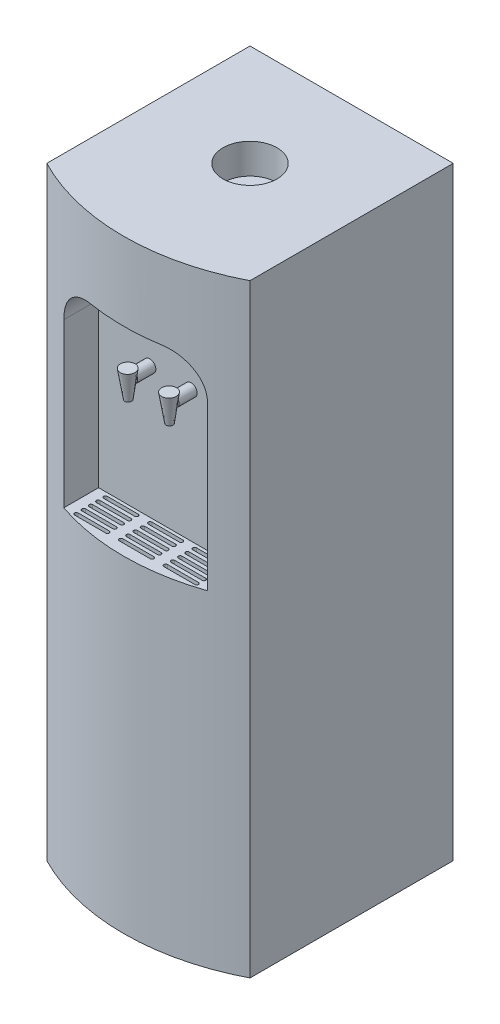
SolidWorks part; units mm, degrees
ref_plane "Front Plane" through (0, 0, 0) normal (0, 0, 1) x (1, 0, 0)
ref_plane "Top Plane" through (0, 0, 0) normal (0, 1, 0) x (1, 0, 0)
ref_plane "Right Plane" through (0, 0, 0) normal (1, 0, 0) x (0, 0, -1)
sketch "Sketch1" plane through (0, 0, 0) normal (0, 1, 0) x (1, 0, 0)
  line L1 (0, 0) -> (42.7396, 0)
  line L2 (0, 0) -> (0, -42.7396)
  line L4 (42.7396, 0) -> (42.7396, -42.7396)
  arc A0 (0, -42.7396) -> (42.7396, -42.7396) centre (21.3698, -1.442) ccw
extrude "Boss-Extrude1" add sketch "Sketch1" along normal blind 127
ref_plane "Plane1" through (0, 0, 127) normal (0, 0, 1) x (1, 0, 0)
sketch "Sketch2" plane through (0, 0, 127) normal (0, 0, 1) x (1, 0, 0)
  line L0 (6.2617, 110.6088) -> (0, 110.6088) construction
  line L1 (13.8817, 110.6088) -> (28.8579, 110.6088)
  line L2 (6.2617, 102.9888) -> (6.2617, 68.7343)
  line L3 (6.2617, 68.7343) -> (36.4779, 68.7343)
  line L4 (36.4779, 102.9888) -> (36.4779, 68.7343)
  line L5 (0, 127) -> (0, 0) construction
  line L6 (36.4779, 110.6088) -> (42.7396, 110.6088) construction
  line L7 (42.7396, 127) -> (42.7396, 0) construction
  arc A0 (28.8579, 110.6088) -> (36.4779, 102.9888) centre (28.8579, 102.9888) cw
  arc A1 (13.8817, 110.6088) -> (6.2617, 102.9888) centre (13.8817, 102.9888) ccw
  dimension "D1" = 7.62
extrude "Cut-Extrude1" cut sketch "Sketch2" against normal blind 88.9
sketch "Sketch4" plane through (0, 68.7343, 0) normal (0, 1, 0) x (1, 0, 0)
  line L0 (6.2617, -38.1) -> (36.4779, -38.1) construction
  line L1 (6.2617, -38.1) -> (36.4779, -38.1) construction
  line L2 (36.4779, -38.1) -> (36.4779, -45.4182) construction
  line L3 (6.2617, -38.1) -> (6.2617, -45.4182) construction
  line L4 (8.7222, -40.6541) -> (15.2596, -40.6541) construction
  line L5 (8.7222, -40.2731) -> (15.2596, -40.2731)
  line L6 (8.7222, -41.0351) -> (15.2596, -41.0351)
  line L7 (18.1011, -40.6541) -> (24.6385, -40.6541) construction
  line L8 (18.1011, -40.2731) -> (24.6385, -40.2731)
  line L9 (18.1011, -41.0351) -> (24.6385, -41.0351)
  line L10 (27.48, -40.6541) -> (34.0174, -40.6541) construction
  line L11 (27.48, -40.2731) -> (34.0174, -40.2731)
  line L12 (27.48, -41.0351) -> (34.0174, -41.0351)
  line L13 (8.3412, -40.6541) -> (6.2617, -40.6541) construction
  line L14 (34.3984, -40.6541) -> (36.4779, -40.6541) construction
  line L15 (15.6406, -40.6541) -> (17.7201, -40.6541) construction
  line L16 (25.0195, -40.6541) -> (27.099, -40.6541) construction
  line L17 (8.7222, -42.1781) -> (15.2596, -42.1781) construction
  line L18 (8.7222, -41.7971) -> (15.2596, -41.7971)
  line L19 (8.7222, -42.5591) -> (15.2596, -42.5591)
  line L20 (18.1011, -42.1781) -> (24.6385, -42.1781) construction
  line L21 (18.1011, -41.7971) -> (24.6385, -41.7971)
  line L22 (18.1011, -42.5591) -> (24.6385, -42.5591)
  line L23 (27.48, -42.1781) -> (34.0174, -42.1781) construction
  line L24 (27.48, -41.7971) -> (34.0174, -41.7971)
  line L25 (27.48, -42.5591) -> (34.0174, -42.5591)
  line L26 (8.7222, -43.7021) -> (15.2596, -43.7021) construction
  line L27 (8.7222, -43.3211) -> (15.2596, -43.3211)
  line L28 (8.7222, -44.0831) -> (15.2596, -44.0831)
  line L29 (18.1011, -43.7021) -> (24.6385, -43.7021) construction
  line L30 (18.1011, -43.3211) -> (24.6385, -43.3211)
  line L31 (18.1011, -44.0831) -> (24.6385, -44.0831)
  line L32 (27.48, -43.7021) -> (34.0174, -43.7021) construction
  line L33 (27.48, -43.3211) -> (34.0174, -43.3211)
  line L34 (27.48, -44.0831) -> (34.0174, -44.0831)
  line L35 (8.7222, -45.2261) -> (15.2596, -45.2261) construction
  line L36 (8.7222, -44.8451) -> (15.2596, -44.8451)
  line L37 (8.7222, -45.6071) -> (15.2596, -45.6071)
  line L38 (18.1011, -45.2261) -> (24.6385, -45.2261) construction
  line L39 (18.1011, -44.8451) -> (24.6385, -44.8451)
  line L40 (18.1011, -45.6071) -> (24.6385, -45.6071)
  line L41 (27.48, -45.2261) -> (34.0174, -45.2261) construction
  line L42 (27.48, -44.8451) -> (34.0174, -44.8451)
  line L43 (27.48, -45.6071) -> (34.0174, -45.6071)
  line L44 (8.7222, -40.6541) -> (15.2596, -40.6541) construction
  line L45 (8.7222, -40.2731) -> (15.2596, -40.2731)
  line L46 (8.7222, -41.0351) -> (15.2596, -41.0351)
  line L47 (18.1011, -40.6541) -> (24.6385, -40.6541) construction
  line L48 (18.1011, -40.2731) -> (24.6385, -40.2731)
  line L49 (18.1011, -41.0351) -> (24.6385, -41.0351)
  line L50 (27.48, -40.6541) -> (34.0174, -40.6541) construction
  line L51 (27.48, -40.2731) -> (34.0174, -40.2731)
  line L52 (27.48, -41.0351) -> (34.0174, -41.0351)
  line L53 (8.7222, -42.1781) -> (15.2596, -42.1781) construction
  line L54 (8.7222, -41.7971) -> (15.2596, -41.7971)
  line L55 (8.7222, -42.5591) -> (15.2596, -42.5591)
  line L56 (18.1011, -42.1781) -> (24.6385, -42.1781) construction
  line L57 (18.1011, -41.7971) -> (24.6385, -41.7971)
  line L58 (18.1011, -42.5591) -> (24.6385, -42.5591)
  line L59 (27.48, -42.1781) -> (34.0174, -42.1781) construction
  line L60 (27.48, -41.7971) -> (34.0174, -41.7971)
  line L61 (27.48, -42.5591) -> (34.0174, -42.5591)
  line L62 (8.7222, -43.7021) -> (15.2596, -43.7021) construction
  line L63 (8.7222, -43.3211) -> (15.2596, -43.3211)
  line L64 (8.7222, -44.0831) -> (15.2596, -44.0831)
  line L65 (18.1011, -43.7021) -> (24.6385, -43.7021) construction
  line L66 (18.1011, -43.3211) -> (24.6385, -43.3211)
  line L67 (18.1011, -44.0831) -> (24.6385, -44.0831)
  line L68 (27.48, -43.7021) -> (34.0174, -43.7021) construction
  line L69 (27.48, -43.3211) -> (34.0174, -43.3211)
  line L70 (27.48, -44.0831) -> (34.0174, -44.0831)
  line L71 (8.7222, -39.1301) -> (15.2596, -39.1301) construction
  line L72 (8.7222, -38.7491) -> (15.2596, -38.7491)
  line L73 (8.7222, -39.5111) -> (15.2596, -39.5111)
  line L74 (18.1011, -39.1301) -> (24.6385, -39.1301) construction
  line L75 (18.1011, -38.7491) -> (24.6385, -38.7491)
  line L76 (18.1011, -39.5111) -> (24.6385, -39.5111)
  line L77 (27.48, -39.1301) -> (34.0174, -39.1301) construction
  line L78 (27.48, -38.7491) -> (34.0174, -38.7491)
  line L79 (27.48, -39.5111) -> (34.0174, -39.5111)
  arc A0 (8.7222, -40.2731) -> (8.7222, -41.0351) centre (8.7222, -40.6541) ccw
  arc A1 (15.2596, -41.0351) -> (15.2596, -40.2731) centre (15.2596, -40.6541) ccw
  arc A2 (18.1011, -40.2731) -> (18.1011, -41.0351) centre (18.1011, -40.6541) ccw
  arc A3 (24.6385, -41.0351) -> (24.6385, -40.2731) centre (24.6385, -40.6541) ccw
  arc A4 (27.48, -40.2731) -> (27.48, -41.0351) centre (27.48, -40.6541) ccw
  arc A5 (34.0174, -41.0351) -> (34.0174, -40.2731) centre (34.0174, -40.6541) ccw
  arc A6 (8.7222, -41.7971) -> (8.7222, -42.5591) centre (8.7222, -42.1781) ccw
  arc A7 (15.2596, -42.5591) -> (15.2596, -41.7971) centre (15.2596, -42.1781) ccw
  arc A8 (18.1011, -41.7971) -> (18.1011, -42.5591) centre (18.1011, -42.1781) ccw
  arc A9 (24.6385, -42.5591) -> (24.6385, -41.7971) centre (24.6385, -42.1781) ccw
  arc A10 (27.48, -41.7971) -> (27.48, -42.5591) centre (27.48, -42.1781) ccw
  arc A11 (34.0174, -42.5591) -> (34.0174, -41.7971) centre (34.0174, -42.1781) ccw
  arc A12 (8.7222, -43.3211) -> (8.7222, -44.0831) centre (8.7222, -43.7021) ccw
  arc A13 (15.2596, -44.0831) -> (15.2596, -43.3211) centre (15.2596, -43.7021) ccw
  arc A14 (18.1011, -43.3211) -> (18.1011, -44.0831) centre (18.1011, -43.7021) ccw
  arc A15 (24.6385, -44.0831) -> (24.6385, -43.3211) centre (24.6385, -43.7021) ccw
  arc A16 (27.48, -43.3211) -> (27.48, -44.0831) centre (27.48, -43.7021) ccw
  arc A17 (34.0174, -44.0831) -> (34.0174, -43.3211) centre (34.0174, -43.7021) ccw
  arc A18 (8.7222, -44.8451) -> (8.7222, -45.6071) centre (8.7222, -45.2261) ccw
  arc A19 (15.2596, -45.6071) -> (15.2596, -44.8451) centre (15.2596, -45.2261) ccw
  arc A20 (18.1011, -44.8451) -> (18.1011, -45.6071) centre (18.1011, -45.2261) ccw
  arc A21 (24.6385, -45.6071) -> (24.6385, -44.8451) centre (24.6385, -45.2261) ccw
  arc A22 (27.48, -44.8451) -> (27.48, -45.6071) centre (27.48, -45.2261) ccw
  arc A23 (34.0174, -45.6071) -> (34.0174, -44.8451) centre (34.0174, -45.2261) ccw
  arc A24 (8.7222, -40.2731) -> (8.7222, -41.0351) centre (8.7222, -40.6541) ccw
  arc A25 (15.2596, -41.0351) -> (15.2596, -40.2731) centre (15.2596, -40.6541) ccw
  arc A26 (18.1011, -40.2731) -> (18.1011, -41.0351) centre (18.1011, -40.6541) ccw
  arc A27 (24.6385, -41.0351) -> (24.6385, -40.2731) centre (24.6385, -40.6541) ccw
  arc A28 (27.48, -40.2731) -> (27.48, -41.0351) centre (27.48, -40.6541) ccw
  arc A29 (34.0174, -41.0351) -> (34.0174, -40.2731) centre (34.0174, -40.6541) ccw
  arc A30 (8.7222, -41.7971) -> (8.7222, -42.5591) centre (8.7222, -42.1781) ccw
  arc A31 (15.2596, -42.5591) -> (15.2596, -41.7971) centre (15.2596, -42.1781) ccw
  arc A32 (18.1011, -41.7971) -> (18.1011, -42.5591) centre (18.1011, -42.1781) ccw
  arc A33 (24.6385, -42.5591) -> (24.6385, -41.7971) centre (24.6385, -42.1781) ccw
  arc A34 (27.48, -41.7971) -> (27.48, -42.5591) centre (27.48, -42.1781) ccw
  arc A35 (34.0174, -42.5591) -> (34.0174, -41.7971) centre (34.0174, -42.1781) ccw
  arc A36 (8.7222, -43.3211) -> (8.7222, -44.0831) centre (8.7222, -43.7021) ccw
  arc A37 (15.2596, -44.0831) -> (15.2596, -43.3211) centre (15.2596, -43.7021) ccw
  arc A38 (18.1011, -43.3211) -> (18.1011, -44.0831) centre (18.1011, -43.7021) ccw
  arc A39 (24.6385, -44.0831) -> (24.6385, -43.3211) centre (24.6385, -43.7021) ccw
  arc A40 (27.48, -43.3211) -> (27.48, -44.0831) centre (27.48, -43.7021) ccw
  arc A41 (34.0174, -44.0831) -> (34.0174, -43.3211) centre (34.0174, -43.7021) ccw
  arc A42 (8.7222, -38.7491) -> (8.7222, -39.5111) centre (8.7222, -39.1301) ccw
  arc A43 (15.2596, -39.5111) -> (15.2596, -38.7491) centre (15.2596, -39.1301) ccw
  arc A44 (18.1011, -38.7491) -> (18.1011, -39.5111) centre (18.1011, -39.1301) ccw
  arc A45 (24.6385, -39.5111) -> (24.6385, -38.7491) centre (24.6385, -39.1301) ccw
  arc A46 (27.48, -38.7491) -> (27.48, -39.5111) centre (27.48, -39.1301) ccw
  arc A47 (34.0174, -39.5111) -> (34.0174, -38.7491) centre (34.0174, -39.1301) ccw
  point P12 (11.9909, -40.6541)
  point P17 (21.3698, -40.6541)
  point P26 (30.7487, -40.6541)
  point P43 (11.9909, -42.1781)
  point P48 (21.3698, -42.1781)
  point P57 (30.7487, -42.1781)
  point P64 (11.9909, -43.7021)
  point P69 (21.3698, -43.7021)
  point P78 (30.7487, -43.7021)
  point P85 (11.9909, -45.2261)
  point P90 (21.3698, -45.2261)
  point P99 (30.7487, -45.2261)
  point P106 (11.9909, -40.6541)
  point P111 (21.3698, -40.6541)
  point P120 (30.7487, -40.6541)
  point P127 (11.9909, -42.1781)
  point P132 (21.3698, -42.1781)
  point P141 (30.7487, -42.1781)
  point P148 (11.9909, -43.7021)
  point P153 (21.3698, -43.7021)
  point P162 (30.7487, -43.7021)
  point P169 (11.9909, -39.1301)
  point P174 (21.3698, -39.1301)
  point P183 (30.7487, -39.1301)
  dimension "D1" = 0.762
  dimension "D2" = 4
  dimension "D3" = 2
extrude "Cut-Extrude2" cut sketch "Sketch4" against normal blind 1.27 contours L40 A21 L39 A20 | L37 A19 L36 A18 | L19 A7 L18 A6 | L28 A13 L27 A12 | L31 A15 L30 A14 | L22 A9 L21 A8 | L9 A3 L8 A2 | L76 A45 L75 A44 | L6 A1 L5 A0 | L73 A43 L72 A42 | L34 A17 L33 A16 | L25 A11 L24 A10 | L12 A5 L11 A4 | L79 A47 L78 A46 | A22 L43 A23 L42
sketch "Sketch5" plane through (0, 127, 0) normal (0, 1, 0) x (1, 0, 0)
  line L0 (0, -21.3698) -> (42.7396, -21.3698)
  line L2 (0, 0) -> (0, -42.7396) construction
  line L4 (42.7396, -42.7396) -> (42.7396, 0) construction
  circle A0 centre (21.3698, -21.3698) radius 5.689
extrude "Cut-Extrude3" cut sketch "Sketch5" against normal blind 6.35 contours L0 A0 | L0 A0
sketch "Sketch6" plane through (0, 0, 38.1) normal (0, 0, 1) x (1, 0, 0)
  line L0 (8.3412, 67.4643) -> (8.3412, 105.8503) construction
  line L1 (34.3984, 67.4643) -> (34.3984, 105.8503) construction
  line L2 (17.0269, 96.3161) -> (8.3412, 96.3161) construction
  line L3 (17.0269, 96.3161) -> (25.7127, 96.3161) construction
  line L4 (25.7127, 96.3161) -> (34.3984, 96.3161) construction
  circle A2 centre (17.0269, 96.3161) radius 1.27
  circle A3 centre (25.7127, 96.3161) radius 1.27
  dimension "D1" = 2.54
extrude "Boss-Extrude2" add sketch "Sketch6" along normal blind 3.81
sketch "Sketch7" plane through (0, 0, 41.91) normal (0, 0, 1) x (1, 0, 0)
  line L0 (17.0269, 95.0461) -> (17.0269, 97.5861) construction
ref_plane "Plane2" through (17.0269, 0, 0) normal (1, 0, 0) x (0, 1, 0)
sketch "Sketch8" plane through (17.0269, 0, 0) normal (1, 0, 0) x (0, 1, 0)
  line L0 (92.4628, 42.6259) -> (92.4628, 43.3418)
  line L2 (92.4628, 43.3418) -> (98.1731, 44.2935)
  line L3 (98.1731, 44.2935) -> (98.1731, 42.7396)
  line L5 (92.4628, 42.6259) -> (98.1731, 42.7396) construction
  line L6 (127, 42.7396) -> (0, 42.7396) construction
  line L7 (92.4628, 42.6259) -> (98.1731, 42.7396)
revolve "Revolve1" add sketch "Sketch8" angle 360 about L5
sketch "Sketch9" plane through (0, 0, 38.1) normal (0, 0, 1) x (1, 0, 0)
  line L0 (21.3698, 110.6088) -> (21.3698, 56.3623) construction
ref_plane "Plane3" through (21.3698, 0, 0) normal (-1, 0, 0) x (0, -1, 0)
mirror "Mirror1" about plane through (21.3698, 0, 0) normal (-1, 0, 0) of "Revolve1"
scale "Scale1" scale about centroid uniform scaling yes scale factor 10
scale "Scale2" scale about centroid uniform scaling yes scale factor 0.8
